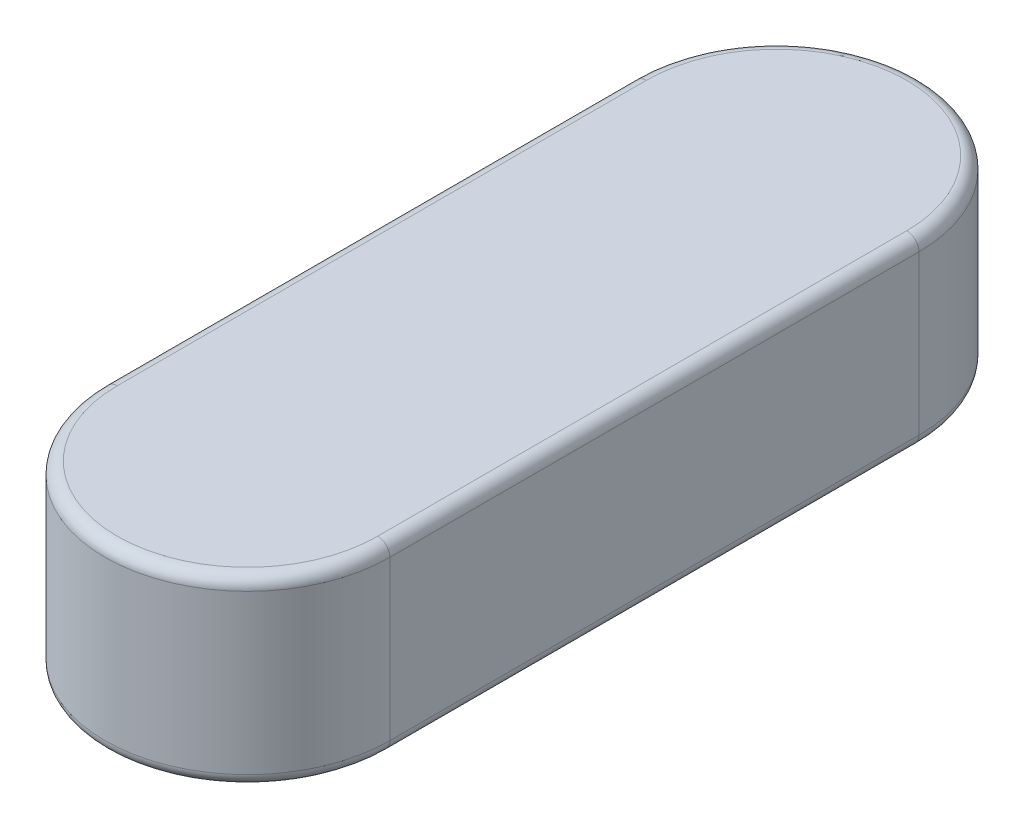
SolidWorks part; units mm, degrees
material "AISI 304"
ref_plane "Спереди" through (0, 0, 0) normal (0, 0, 1) x (1, 0, 0)
ref_plane "Сверху" through (0, 0, 0) normal (0, 1, 0) x (1, 0, 0)
ref_plane "Справа" through (0, 0, 0) normal (1, 0, 0) x (0, 0, -1)
sketch "Эскиз1" plane through (0, 0, 0) normal (0, 1, 0) x (1, 0, 0)
  line L0 (0, 0) -> (0, 26) construction
  line L1 (-7, 0) -> (-7, 26)
  line L2 (7, 0) -> (7, 26)
  line L3 (0, -7) -> (0, 33) construction
  arc A0 (-7, 0) -> (7, 0) centre (0, 0) ccw
  arc A1 (7, 26) -> (-7, 26) centre (0, 26) ccw
  point P3 (0, 13)
  dimension "D1" = 7
  dimension "D2" = 26
  dimension "D3" = 40
  dimension "D4" = 14
extrude "Бобышка-Вытянуть1" add sketch "Эскиз1" along normal blind 9
fillet "Скругление1" radius 0.6 8 edges at (7, 0, -13) (0, 0, -33) (-7, 0, -13) (0, 0, 7) (-7, 9, -13) (0, 9, -33) (7, 9, -13) (0, 9, 7)
